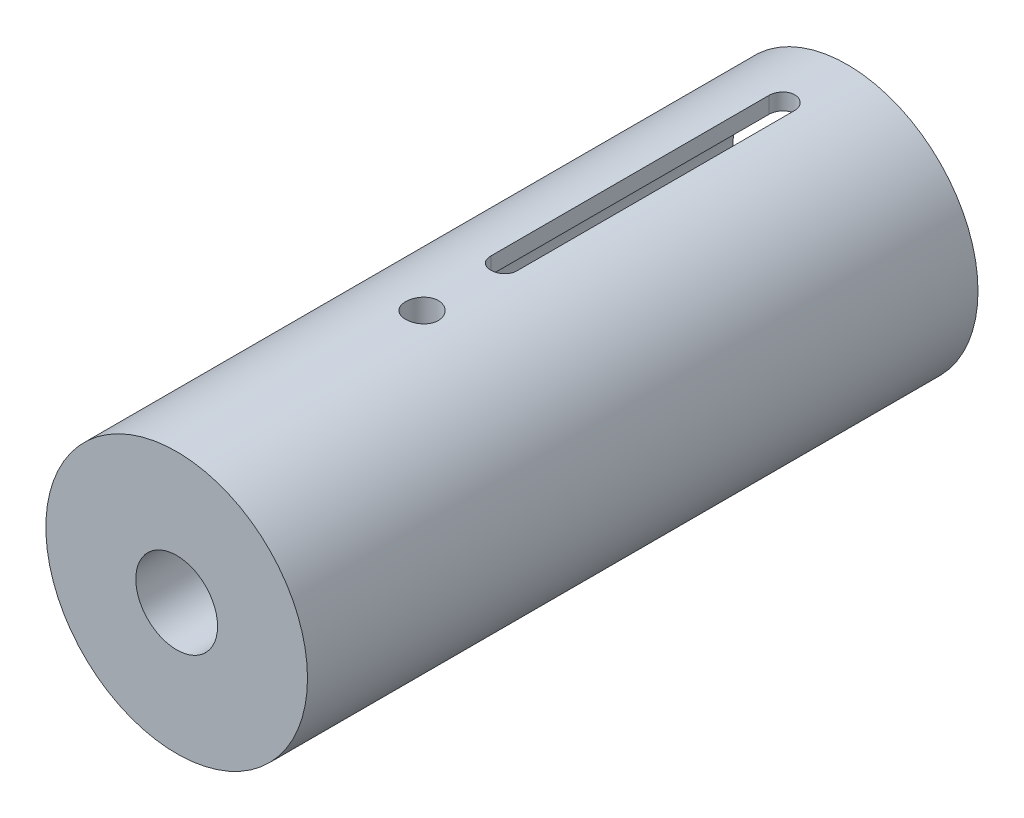
SolidWorks part; units mm, degrees
ref_plane "Front Plane" through (0, 0, 0) normal (0, 0, 1) x (1, 0, 0)
ref_plane "Top Plane" through (0, 0, 0) normal (0, 1, 0) x (1, 0, 0)
ref_plane "Right Plane" through (0, 0, 0) normal (1, 0, 0) x (0, 0, -1)
sketch "Sketch1" plane through (0, 0, 0) normal (0, 0, 1) x (1, 0, 0)
  circle A0 centre (0, 0) radius 7
  circle A1 centre (0, 0) radius 8
  dimension "D1" = 16
  dimension "D2" = 14
extrude "Boss-Extrude1" add sketch "Sketch1" along normal blind 41
sketch "Sketch2" plane through (0, 0, 0) normal (0, 1, 0) x (1, 0, 0)
  line L0 (8, 0) -> (-8, 0) construction
  line L2 (-0.7937, -4) -> (-0.7938, -21)
  line L4 (0.7937, -4) -> (0.7938, -21)
  arc A0 (-0.7937, -4) -> (0.7937, -4) centre (0, -4) cw
  arc A1 (-0.7938, -21) -> (0.7938, -21) centre (0, -21) ccw
  point P4 (0.6654, -1.9924)
  point P7 (0, 0)
  point P9 (0.7938, -2.5724)
  point P11 (0.7937, -20.6748)
  dimension "D1" = 1.5875
  dimension "D2" = 17
  dimension "D3" = 21
extrude "Cut-Extrude1" cut sketch "Sketch2" against normal through all and the other way through all
sketch "Sketch3" plane through (0, 0, 41) normal (0, 0, 1) x (1, 0, 0)
  circle A0 centre (0, 0) radius 7
  circle A1 centre (0, 0) radius 2.5
  dimension "D1" = 5
  dimension "D2" = 14
extrude "Boss-Extrude2" add sketch "Sketch3" against normal blind 17
sketch "Sketch4" plane through (0, 0, 0) normal (0, 1, 0) x (1, 0, 0)
  line L0 (-2.5, -41) -> (2.5, -41) construction
  line L1 (-2.5, -41) -> (2.5, -41) construction
  circle A0 centre (0, -26) radius 1
  point P2 (0, 0)
  dimension "D1" = 2
  dimension "D2" = 15
extrude "Cut-Extrude2" cut sketch "Sketch4" along normal blind 17
